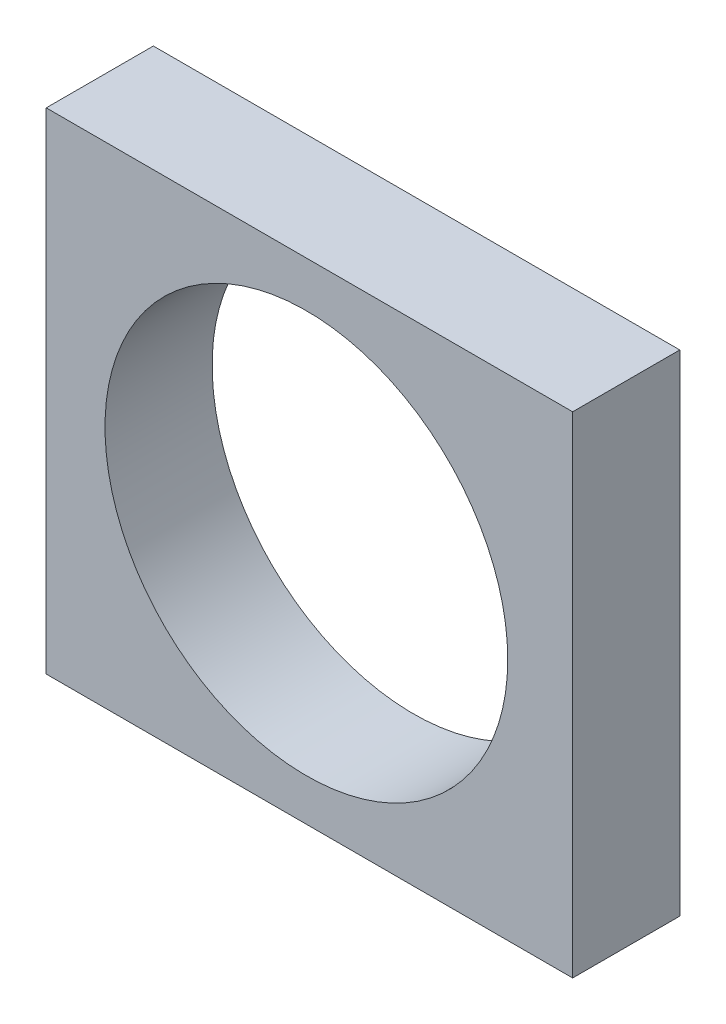
SolidWorks part; units mm, degrees
ref_plane "Plan de face" through (0, 0, 0) normal (0, 0, 1) x (1, 0, 0)
ref_plane "Plan de dessus" through (0, 0, 0) normal (0, 1, 0) x (1, 0, 0)
ref_plane "Plan de droite" through (0, 0, 0) normal (1, 0, 0) x (0, 0, -1)
sketch "Esquisse1" plane through (0, 0, 0) normal (0, 0, 1) x (1, 0, 0)
  line L1 (-12.1435, 11.5291) -> (12.4296, 11.5291)
  line L2 (-12.1435, 11.5291) -> (-12.1435, -11.3608)
  line L3 (-12.1435, -11.3608) -> (12.4296, -11.3608)
  line L4 (12.4296, 11.5291) -> (12.4296, -11.3608)
  circle A0 centre (0, 0) radius 9.4
  point P7 (-12.1435, 11.5291)
  point P8 (12.4296, -11.3608)
  dimension "D1" = 18.8
extrude "Boss.-Extru.1" add sketch "Esquisse1" along normal blind 5
